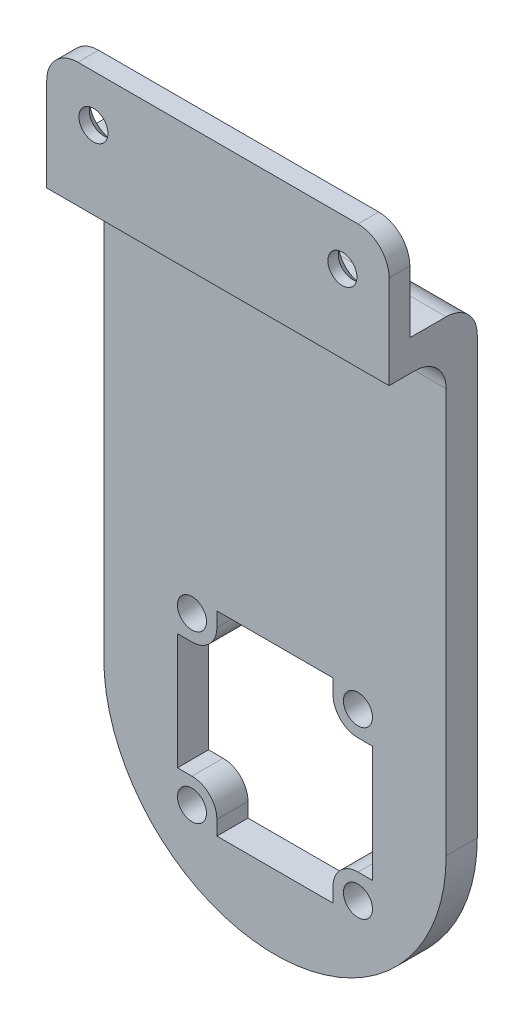
SolidWorks part; units mm, degrees
ref_plane "Front Plane" through (0, 0, 0) normal (0, 0, 1) x (1, 0, 0)
ref_plane "Top Plane" through (0, 0, 0) normal (0, 1, 0) x (1, 0, 0)
ref_plane "Right Plane" through (0, 0, 0) normal (1, 0, 0) x (0, 0, -1)
sketch "Sketch1" plane through (0, 0, 0) normal (0, 0, 1) x (1, 0, 0)
  line L0 (-1.8889, 0.3815) -> (-1.8889, 1.7815)
  line L1 (-1.8889, 1.7815) -> (9.3111, 1.7815)
  line L2 (-4.2889, -2.0185) -> (-5.6889, -2.0185)
  line L3 (13.1111, -2.0185) -> (13.1111, -13.2185)
  line L4 (11.7111, -2.0185) -> (13.1111, -2.0185)
  line L5 (9.3111, 0.3815) -> (9.3111, 1.7815)
  line L6 (9.3111, -17.0185) -> (-1.8889, -17.0185)
  line L7 (9.3111, -15.6185) -> (9.3111, -17.0185)
  line L8 (11.7111, -13.2185) -> (13.1111, -13.2185)
  line L9 (-5.6889, -13.2185) -> (-5.6889, -2.0185)
  line L10 (-4.2889, -13.2185) -> (-5.6889, -13.2185)
  line L11 (-1.8889, -15.6185) -> (-1.8889, -17.0185)
  circle A0 centre (-4.2889, 0.3815) radius 1.4
  circle A1 centre (-4.2889, 0.3815) radius 2.4
  circle A2 centre (3.7111, -7.6185) radius 16.5
  circle A3 centre (11.7111, 0.3815) radius 1.4
  circle A4 centre (11.7111, 0.3815) radius 2.4
  circle A5 centre (11.7111, -15.6185) radius 1.4
  circle A6 centre (11.7111, -15.6185) radius 2.4
  circle A7 centre (-4.2889, -15.6185) radius 1.4
  circle A8 centre (-4.2889, -15.6185) radius 2.4
  point P37 (3.7111, -7.6185)
  dimension "D1" = 2.8
  dimension "D2" = 4.8
  dimension "D6" = 9.4
  dimension "D7" = 33
  dimension "D3" = 1.4
  dimension "D4" = 11.2
  dimension "D5" = 1.4
  dimension "D8" = 4
extrude "Boss-Extrude1" add sketch "Sketch1" along normal blind 3 contours A4 A3 | A1 A0 | A8 A7 | A6 A5 | A2 A8 L10 L9 L2 A1 L0 L1 L5 A4 L4 L3 L8 A6 L7 L6 L11
sketch "Sketch3" plane through (0, 0, 3) normal (0, 0, 1) x (1, 0, 0)
  line L1 (-12.7889, -7.6185) -> (20.2111, -7.6185)
  line L2 (-12.7889, -7.6185) -> (-12.7889, 46.3815)
  line L3 (-12.7889, 46.3815) -> (20.2111, 46.3815)
  line L4 (20.2111, -7.6185) -> (20.2111, 46.3815)
  circle A0 centre (3.7111, -7.6185) radius 16.5 construction
  circle A1 centre (-8.2889, 41.8815) radius 1.4
  circle A2 centre (15.7111, 41.8815) radius 1.4
  circle A3 centre (3.7111, -7.6185) radius 16.5
  circle M22 centre (3.7111, -7.6185) radius 16.5
  dimension "D2" = 2.8
  dimension "D3" = 2.8
  dimension "D4" = 49.5
  dimension "D5" = 49.5
  dimension "D6" = 12
  dimension "D7" = 12
  dimension "D1" = 54
extrude "Boss-Extrude2" add sketch "Sketch3" against normal blind 3 contours L4 L3 L2 A2 A1 M22
sketch "Sketch4" plane through (0, 0, 3) normal (0, 0, 1) x (1, 0, 0)
  line L0 (20.2111, -7.6185) -> (20.2111, 46.3815) construction
  line L1 (-12.7889, 46.3815) -> (20.2111, 46.3815)
  line L2 (-12.7889, 46.3815) -> (-12.7889, 34.3815)
  line L3 (-12.7889, 34.3815) -> (20.2111, 34.3815)
  line L4 (20.2111, 46.3815) -> (20.2111, 34.3815)
  circle A0 centre (-8.2889, 41.8815) radius 1.4 construction
  circle A1 centre (-8.2889, 41.8815) radius 1.4
  circle A2 centre (15.7111, 41.8815) radius 1.4
  dimension "D1" = 7.5
extrude "Boss-Extrude3" add sketch "Sketch4" along normal blind 5.5
sketch "Sketch5" plane through (0, 0, 0) normal (0, 0, -1) x (-1, 0, 0)
  line L0 (12.7889, -7.6185) -> (12.7889, 46.3815) construction
  line L1 (-20.2111, 46.3815) -> (12.7889, 46.3815)
  line L2 (-20.2111, 46.3815) -> (-20.2111, 37.3815)
  line L3 (-20.2111, 37.3815) -> (12.7889, 37.3815)
  line L4 (12.7889, 46.3815) -> (12.7889, 37.3815)
  circle A0 centre (-15.7111, 41.8815) radius 1.4 construction
  dimension "D1" = 4.5
extrude "Cut-Extrude1" cut sketch "Sketch5" against normal blind 6.5
fillet "Fillet1" radius 3 4 edges at (-12.7889, 46.3815, 7.5) (20.2111, 46.3815, 7.5) (3.7111, 34.3815, 3) (3.7111, 37.3815, 0)
chamfer "Chamfer1" distance 1 angle 45 2 edges at (-9.6889, 41.8815, 6.5) (14.3111, 41.8815, 6.5)
